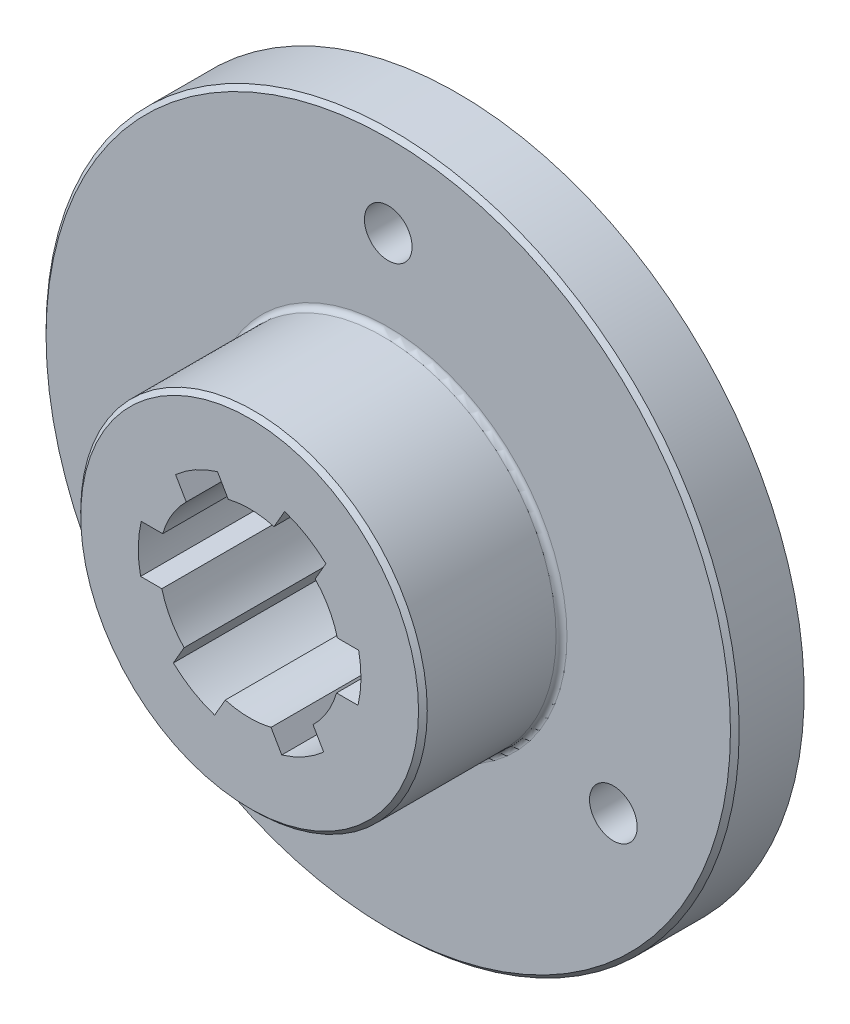
SolidWorks part; units mm, degrees
ref_plane "Front Plane" through (0, 0, 0) normal (0, 0, 1) x (1, 0, 0)
ref_plane "Top Plane" through (0, 0, 0) normal (0, 1, 0) x (1, 0, 0)
ref_plane "Right Plane" through (0, 0, 0) normal (1, 0, 0) x (0, 0, -1)
sketch "Sketch1" plane through (0, 0, 0) normal (0, 1, 0) x (1, 0, 0)
  line L0 (38.1, 3.175) -> (0, 3.175)
  line L1 (0, 3.175) -> (0, -3.175)
  line L2 (0, -3.175) -> (38.1, -3.175)
  line L3 (38.1, -3.175) -> (38.1, 3.175)
  line L4 (0, 3.175) -> (0, -3.175) construction
revolve "Revolve1" add sketch "Sketch1" angle 360 about L4
sketch "Sketch2" plane through (0, 0, 3.175) normal (0, 0, 1) x (1, 0, 0)
  circle A0 centre (0, 0) radius 15.875
extrude "Boss-Extrude1" add sketch "Sketch2" along normal blind 12.7
sketch "Sketch3" plane through (0, 0, 15.875) normal (0, 0, 1) x (1, 0, 0)
  line L0 (-7.8136, 2.1348) -> (-9.7695, 2.1348)
  line L1 (-9.8245, -1.8652) -> (-7.8823, -1.8652)
  line L2 (-5.7556, -5.6994) -> (-6.7336, -7.3932)
  line L3 (-3.297, -9.4409) -> (-2.3259, -7.7589)
  line L4 (2.058, -7.8342) -> (3.0359, -9.528)
  line L5 (6.5275, -7.5757) -> (5.5564, -5.8937)
  line L6 (7.8136, -2.1348) -> (9.7695, -2.1348)
  line L7 (9.8245, 1.8652) -> (7.8823, 1.8652)
  line L8 (5.7556, 5.6994) -> (6.7336, 7.3932)
  line L9 (3.297, 9.4409) -> (2.3259, 7.7589)
  line L10 (-2.058, 7.8342) -> (-3.0359, 9.528)
  line L11 (-6.5275, 7.5757) -> (-5.5564, 5.8937)
  arc A0 (-5.5564, 5.8937) -> (-7.8136, 2.1348) centre (0, 0) ccw
  arc A1 (-9.7695, 2.1348) -> (-9.8245, -1.8652) centre (0, 0) ccw
  arc A2 (-7.8823, -1.8652) -> (-5.7556, -5.6994) centre (0, 0) ccw
  arc A3 (-6.7336, -7.3932) -> (-3.297, -9.4409) centre (0, 0) ccw
  arc A4 (-2.3259, -7.7589) -> (2.058, -7.8342) centre (0, 0) ccw
  arc A5 (3.0359, -9.528) -> (6.5275, -7.5757) centre (0, 0) ccw
  arc A6 (5.5564, -5.8937) -> (7.8136, -2.1348) centre (0, 0) ccw
  arc A7 (9.7695, -2.1348) -> (9.8245, 1.8652) centre (0, 0) ccw
  arc A8 (7.8823, 1.8652) -> (5.7556, 5.6994) centre (0, 0) ccw
  arc A9 (6.7336, 7.3932) -> (3.297, 9.4409) centre (0, 0) ccw
  arc A10 (2.3259, 7.7589) -> (-2.058, 7.8342) centre (0, 0) ccw
  arc A11 (-3.0359, 9.528) -> (-6.5275, 7.5757) centre (0, 0) ccw
  dimension "D1" = 10
  dimension "D2" = 8.1
  dimension "D3" = 4
extrude "Cut-Extrude1" cut sketch "Sketch3" against normal blind 14.986
sketch "Sketch10" plane through (0, 0, 0.889) normal (0, 0, 1) x (1, 0, 0)
  circle A0 centre (0, 0) radius 4
  dimension "D1" = 8
extrude "Cut-Extrude3" cut sketch "Sketch10" against normal blind 10
fillet "Fillet2" radius 0.5 1 edges at (15.875, 0, 3.175)
sketch "Sketch11" plane through (0, 0, 15.875) normal (0, 0, 1) x (1, 0, 0)
  line L0 (-6.5275, 7.5757) -> (-5.5564, 5.8937) construction
  line L1 (3.297, 9.4409) -> (2.3259, 7.7589) construction
  line L2 (5.7556, 5.6994) -> (6.7336, 7.3932) construction
  line L3 (9.8245, 1.8652) -> (7.8823, 1.8652) construction
  line L4 (7.8136, -2.1348) -> (9.7695, -2.1348) construction
  line L5 (6.5275, -7.5757) -> (5.5564, -5.8937) construction
  line L6 (2.058, -7.8342) -> (3.0359, -9.528) construction
  line L7 (-3.297, -9.4409) -> (-2.3259, -7.7589) construction
  line L8 (-6.5275, 7.5757) -> (-5.5564, 5.8937)
  line L9 (3.297, 9.4409) -> (2.3259, 7.7589)
  line L10 (5.7556, 5.6994) -> (6.7336, 7.3932)
  line L11 (9.8245, 1.8652) -> (7.8823, 1.8652)
  line L12 (-6.5275, 7.5757) -> (-5.5564, 5.8937)
  line L13 (-2.058, 7.8342) -> (-3.0359, 9.528)
  line L14 (3.297, 9.4409) -> (2.3259, 7.7589)
  line L15 (5.7556, 5.6994) -> (6.7336, 7.3932)
  line L16 (9.8245, 1.8652) -> (7.8823, 1.8652)
  line L17 (7.8136, -2.1348) -> (9.7695, -2.1348)
  line L18 (6.5275, -7.5757) -> (5.5564, -5.8937)
  line L19 (2.058, -7.8342) -> (3.0359, -9.528)
  line L20 (-3.297, -9.4409) -> (-2.3259, -7.7589)
  line L21 (-5.7556, -5.6994) -> (-6.7336, -7.3932)
  line L22 (-9.8245, -1.8652) -> (-7.8823, -1.8652)
  line L23 (-7.8136, 2.1348) -> (-9.7695, 2.1348)
  line L24 (-6.5275, 7.5757) -> (-5.5564, 5.8937)
  line L25 (-2.058, 7.8342) -> (-3.0359, 9.528)
  line L26 (3.297, 9.4409) -> (2.3259, 7.7589)
  line L27 (5.7556, 5.6994) -> (6.7336, 7.3932)
  line L28 (9.8245, 1.8652) -> (7.8823, 1.8652)
  line L29 (7.8136, -2.1348) -> (9.7695, -2.1348)
  line L30 (6.5275, -7.5757) -> (5.5564, -5.8937)
  line L31 (2.058, -7.8342) -> (3.0359, -9.528)
  line L32 (-3.297, -9.4409) -> (-2.3259, -7.7589)
  line L33 (-5.7556, -5.6994) -> (-6.7336, -7.3932)
  line L34 (-9.8245, -1.8652) -> (-7.8823, -1.8652)
  line L35 (-7.8136, 2.1348) -> (-9.7695, 2.1348)
  line L36 (7.8136, -2.1348) -> (9.7695, -2.1348)
  line L37 (6.5275, -7.5757) -> (5.5564, -5.8937)
  line L38 (2.058, -7.8342) -> (3.0359, -9.528)
  line L39 (-3.297, -9.4409) -> (-2.3259, -7.7589)
  line L40 (-9.9888, -2.0652) -> (-8.039, -2.0652)
  line L41 (-6.0045, -5.7303) -> (-6.9866, -7.4315)
  line L42 (-3.2059, -9.6831) -> (-2.231, -7.9945)
  line L43 (1.9604, -8.0652) -> (2.9426, -9.7663)
  line L44 (6.7829, -7.6179) -> (5.808, -5.9294)
  line L45 (7.9648, -2.3348) -> (9.9292, -2.3348)
  line L46 (9.9888, 2.0652) -> (8.039, 2.0652)
  line L47 (6.0045, 5.7303) -> (6.9866, 7.4315)
  line L48 (3.2059, 9.6831) -> (2.231, 7.9945)
  line L49 (-1.9604, 8.0652) -> (-2.9426, 9.7663)
  line L50 (-6.7829, 7.6179) -> (-5.808, 5.9294)
  line L51 (-7.9648, 2.3348) -> (-9.9292, 2.3348)
  arc A0 (2.3259, 7.7589) -> (-2.058, 7.8342) centre (0, 0) ccw construction
  arc A1 (2.3259, 7.7589) -> (-2.058, 7.8342) centre (0, 0) ccw
  arc A2 (-3.0359, 9.528) -> (-6.5275, 7.5757) centre (0, 0) ccw construction
  arc A3 (-9.9292, 2.3348) -> (-9.9888, -2.0652) centre (0, 0) ccw
  arc A4 (-8.039, -2.0652) -> (-6.0045, -5.7303) centre (0, 0) ccw
  arc A5 (-5.5564, 5.8937) -> (-7.8136, 2.1348) centre (0, 0) ccw construction
  arc A6 (6.7336, 7.3932) -> (3.297, 9.4409) centre (0, 0) ccw construction
  arc A7 (7.8823, 1.8652) -> (5.7556, 5.6994) centre (0, 0) ccw construction
  arc A8 (9.7695, -2.1348) -> (9.8245, 1.8652) centre (0, 0) ccw construction
  arc A9 (5.5564, -5.8937) -> (7.8136, -2.1348) centre (0, 0) ccw construction
  arc A10 (3.0359, -9.528) -> (6.5275, -7.5757) centre (0, 0) ccw construction
  arc A11 (-2.3259, -7.7589) -> (2.058, -7.8342) centre (0, 0) ccw construction
  arc A12 (-6.7336, -7.3932) -> (-3.297, -9.4409) centre (0, 0) ccw construction
  arc A13 (-3.0359, 9.528) -> (-6.5275, 7.5757) centre (0, 0) ccw
  arc A14 (-5.5564, 5.8937) -> (-7.8136, 2.1348) centre (0, 0) ccw
  arc A15 (6.7336, 7.3932) -> (3.297, 9.4409) centre (0, 0) ccw
  arc A16 (-5.5564, 5.8937) -> (-7.8136, 2.1348) centre (0, 0) ccw
  arc A17 (-3.0359, 9.528) -> (-6.5275, 7.5757) centre (0, 0) ccw
  arc A18 (2.3259, 7.7589) -> (-2.058, 7.8342) centre (0, 0) ccw
  arc A19 (6.7336, 7.3932) -> (3.297, 9.4409) centre (0, 0) ccw
  arc A20 (7.8823, 1.8652) -> (5.7556, 5.6994) centre (0, 0) ccw
  arc A21 (9.7695, -2.1348) -> (9.8245, 1.8652) centre (0, 0) ccw
  arc A22 (5.5564, -5.8937) -> (7.8136, -2.1348) centre (0, 0) ccw
  arc A23 (3.0359, -9.528) -> (6.5275, -7.5757) centre (0, 0) ccw
  arc A24 (-2.3259, -7.7589) -> (2.058, -7.8342) centre (0, 0) ccw
  arc A25 (-6.7336, -7.3932) -> (-3.297, -9.4409) centre (0, 0) ccw
  arc A26 (-7.8823, -1.8652) -> (-5.7556, -5.6994) centre (0, 0) ccw
  arc A27 (-9.7695, 2.1348) -> (-9.8245, -1.8652) centre (0, 0) ccw
  arc A28 (-5.5564, 5.8937) -> (-7.8136, 2.1348) centre (0, 0) ccw
  arc A29 (-3.0359, 9.528) -> (-6.5275, 7.5757) centre (0, 0) ccw
  arc A30 (2.3259, 7.7589) -> (-2.058, 7.8342) centre (0, 0) ccw
  arc A31 (6.7336, 7.3932) -> (3.297, 9.4409) centre (0, 0) ccw
  arc A32 (7.8823, 1.8652) -> (5.7556, 5.6994) centre (0, 0) ccw
  arc A33 (9.7695, -2.1348) -> (9.8245, 1.8652) centre (0, 0) ccw
  arc A34 (5.5564, -5.8937) -> (7.8136, -2.1348) centre (0, 0) ccw
  arc A35 (3.0359, -9.528) -> (6.5275, -7.5757) centre (0, 0) ccw
  arc A36 (-2.3259, -7.7589) -> (2.058, -7.8342) centre (0, 0) ccw
  arc A37 (-6.7336, -7.3932) -> (-3.297, -9.4409) centre (0, 0) ccw
  arc A38 (-7.8823, -1.8652) -> (-5.7556, -5.6994) centre (0, 0) ccw
  arc A39 (-9.7695, 2.1348) -> (-9.8245, -1.8652) centre (0, 0) ccw
  arc A40 (7.8823, 1.8652) -> (5.7556, 5.6994) centre (0, 0) ccw
  arc A41 (9.7695, -2.1348) -> (9.8245, 1.8652) centre (0, 0) ccw
  arc A42 (5.5564, -5.8937) -> (7.8136, -2.1348) centre (0, 0) ccw
  arc A43 (3.0359, -9.528) -> (6.5275, -7.5757) centre (0, 0) ccw
  arc A44 (-2.3259, -7.7589) -> (2.058, -7.8342) centre (0, 0) ccw
  arc A45 (-6.7336, -7.3932) -> (-3.297, -9.4409) centre (0, 0) ccw
  arc A46 (-6.9866, -7.4315) -> (-3.2059, -9.6831) centre (0, 0) ccw
  arc A47 (-2.231, -7.9945) -> (1.9604, -8.0652) centre (0, 0) ccw
  arc A48 (2.9426, -9.7663) -> (6.7829, -7.6179) centre (0, 0) ccw
  arc A49 (5.808, -5.9294) -> (7.9648, -2.3348) centre (0, 0) ccw
  arc A50 (9.9292, -2.3348) -> (9.9888, 2.0652) centre (0, 0) ccw
  arc A51 (8.039, 2.0652) -> (6.0045, 5.7303) centre (0, 0) ccw
  arc A52 (6.9866, 7.4315) -> (3.2059, 9.6831) centre (0, 0) ccw
  arc A53 (2.231, 7.9945) -> (-1.9604, 8.0652) centre (0, 0) ccw
  arc A54 (-2.9426, 9.7663) -> (-6.7829, 7.6179) centre (0, 0) ccw
  arc A55 (-5.808, 5.9294) -> (-7.9648, 2.3348) centre (0, 0) ccw
  arc M30 (-7.8136, 2.1348) -> (-5.5564, 5.8937) centre (0, 0) cw
  line M31 (-5.5564, 5.8937) -> (-6.5275, 7.5757)
  arc M32 (-6.5275, 7.5757) -> (-3.0359, 9.528) centre (0, 0) cw
  line M33 (-3.0359, 9.528) -> (-2.058, 7.8342)
  arc M34 (-2.058, 7.8342) -> (2.3259, 7.7589) centre (0, 0) cw
  line M35 (2.3259, 7.7589) -> (3.297, 9.4409)
  arc M36 (3.297, 9.4409) -> (6.7336, 7.3932) centre (0, 0) cw
  line M37 (6.7336, 7.3932) -> (5.7556, 5.6994)
  arc M38 (5.7556, 5.6994) -> (7.8823, 1.8652) centre (0, 0) cw
  line M39 (7.8823, 1.8652) -> (9.8245, 1.8652)
  arc M40 (9.8245, 1.8652) -> (9.7695, -2.1348) centre (0, 0) cw
  line M41 (9.7695, -2.1348) -> (7.8136, -2.1348)
  arc M42 (7.8136, -2.1348) -> (5.5564, -5.8937) centre (0, 0) cw
  line M43 (5.5564, -5.8937) -> (6.5275, -7.5757)
  arc M44 (6.5275, -7.5757) -> (3.0359, -9.528) centre (0, 0) cw
  line M45 (3.0359, -9.528) -> (2.058, -7.8342)
  arc M46 (2.058, -7.8342) -> (-2.3259, -7.7589) centre (0, 0) cw
  line M47 (-2.3259, -7.7589) -> (-3.297, -9.4409)
  arc M48 (-3.297, -9.4409) -> (-6.7336, -7.3932) centre (0, 0) cw
  line M49 (-6.7336, -7.3932) -> (-5.7556, -5.6994)
  arc M50 (-5.7556, -5.6994) -> (-7.8823, -1.8652) centre (0, 0) cw
  line M51 (-7.8823, -1.8652) -> (-9.8245, -1.8652)
  arc M52 (-9.8245, -1.8652) -> (-9.7695, 2.1348) centre (0, 0) cw
  line M53 (-9.7695, 2.1348) -> (-7.8136, 2.1348)
  dimension "D1" = 0.2
  dimension "D2" = 0
sketch "Sketch12" plane through (0, 0, -3.175) normal (0, 0, -1) x (-1, 0, 0)
  circle A0 centre (0, 0) radius 23.8125 construction
  circle A1 centre (0, 23.8125) radius 2.1828
  circle A2 centre (20.6222, -11.9062) radius 2.1828
  circle A3 centre (-20.6222, -11.9063) radius 2.1828
  circle A4 centre (0, 0) radius 38.1271
  circle A5 centre (0, 0) radius 31.75
  point P11 (0, 0)
  circle M2 centre (0, 0) radius 38.1
  dimension "D1" = 47.625
  dimension "D2" = 4.3656
  dimension "D4" = 63.5
  dimension "D3" = 3
extrude "Cut-Extrude8" cut sketch "Sketch12" against normal blind 10 contours A5 M2 | A1 | A3 | A2
chamfer "Chamfer1" distance 0.4 angle 45 2 edges at (31.75, 0, 3.175) (15.875, 0, 15.875)
sketch "Sketch13" plane through (0, 0, -3.175) normal (0, 0, -1) x (-1, 0, 0)
  circle A0 centre (0, 0) radius 9.09
  dimension "D1" = 18.18
extrude "Cut-Extrude9" cut sketch "Sketch13" against normal blind 2.54
extrude "Cut-Extrude10" cut sketch "Sketch11" against normal up to surface (14.986 mm away) contours L50 A55 L51 A3 L40 A4 L41 A46 L42 A47 L43 A48 L44 A49 L45 A50 L46 A51 L47 A52 L48 A53 L49 A54 M53 M30 M31 M32 M33 M34 M35 M36 M37 M38 M39 M40 M41 M42 M43 M44 M45 M46 M47 M48 M49 M50 M51 M52 up to face at (4, 0, 0.889)
